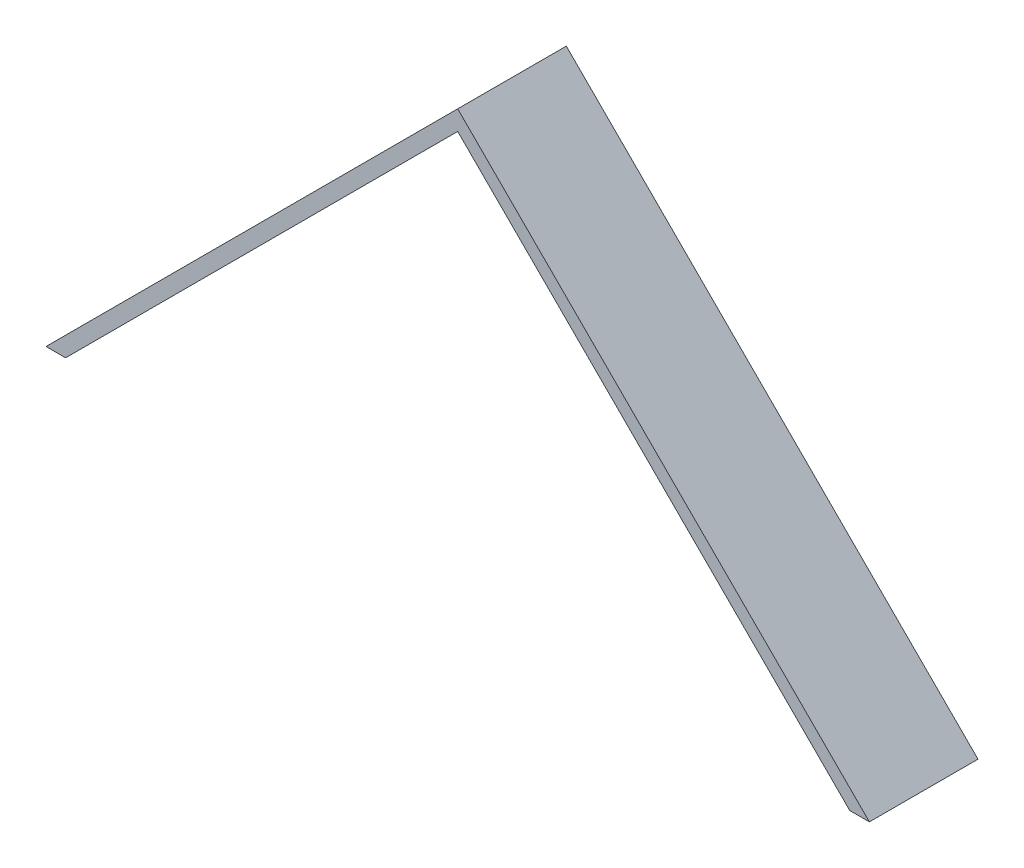
SolidWorks part; units mm, degrees
ref_plane "Front Plane" through (0, 0, 0) normal (0, 0, 1) x (1, 0, 0)
ref_plane "Top Plane" through (0, 0, 0) normal (0, 1, 0) x (1, 0, 0)
ref_plane "Right Plane" through (0, 0, 0) normal (1, 0, 0) x (0, 0, -1)
sketch "Sketch1" plane through (0, 0, 0) normal (0, 0, 1) x (1, 0, 0)
  line L0 (0, 565.6854) -> (-565.6854, 0)
  line L1 (0, 565.6854) -> (565.6854, 0)
  line L2 (0, 0) -> (0, 62.5693) construction
  line L3 (392.4368, 0) -> (-388.4392, 0) construction
  line L4 (0, 538.7447) -> (538.7447, 0)
  line L5 (0, 538.7447) -> (-538.7447, 0)
  line L6 (-565.6854, 0) -> (-538.7447, 0)
  line L7 (565.6854, 0) -> (538.7447, 0)
  line L8 (0, 538.7447) -> (-552.215, -13.4704) construction
  line L9 (0, 538.7447) -> (552.215, -13.4704) construction
  dimension "D1" = 90
  dimension "D2" = 800
  dimension "D3" = 19.05
extrude "Boss-Extrude1" add sketch "Sketch1" along normal blind 149.225
